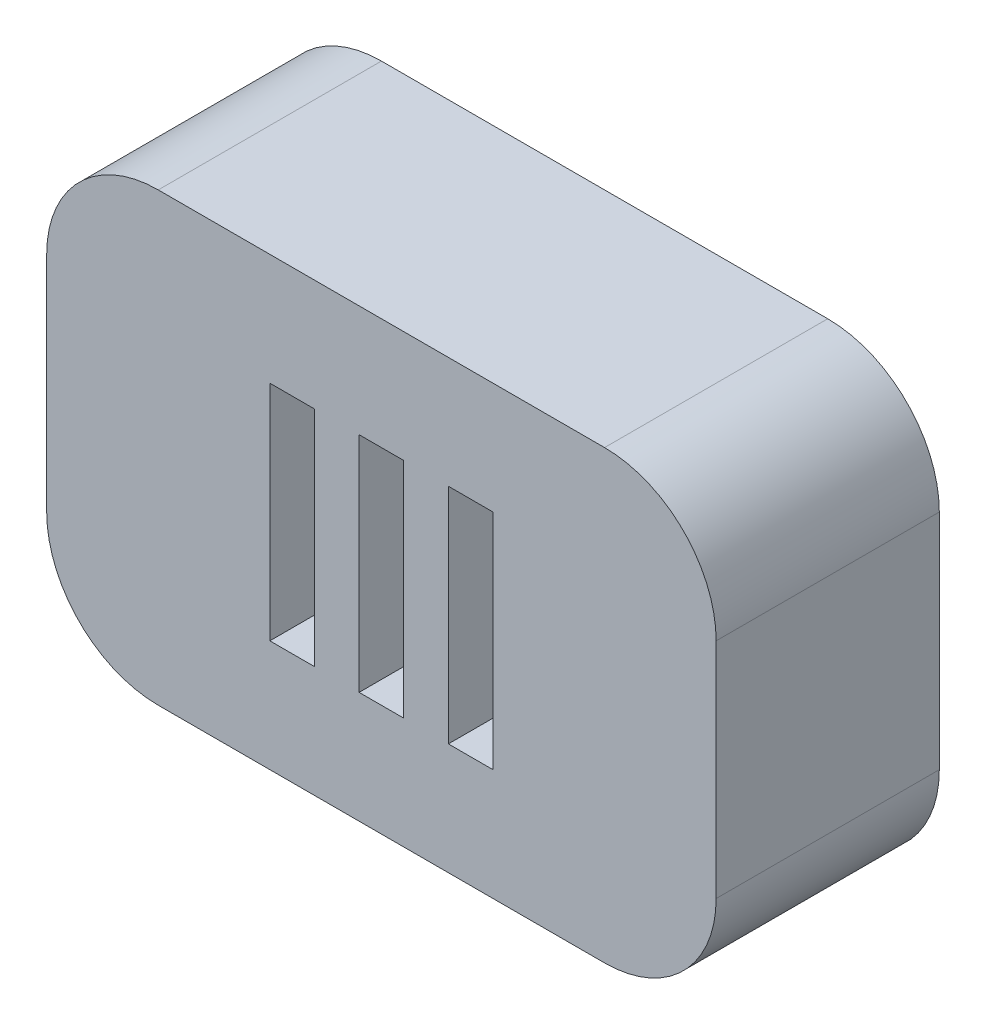
SolidWorks part; units mm, degrees
material "PVC hart"
ref_plane "Ebene vorne" through (0, 0, 0) normal (0, 0, 1) x (1, 0, 0)
ref_plane "Ebene oben" through (0, 0, 0) normal (0, 1, 0) x (1, 0, 0)
ref_plane "Ebene rechts" through (0, 0, 0) normal (1, 0, 0) x (0, 0, -1)
sketch "Skizze1" plane through (0, 0, 0) normal (0, 0, 1) x (1, 0, 0)
  line L1 (1, 0) -> (5, 0)
  line L2 (0, 1) -> (0, 3)
  line L3 (1, 4) -> (5, 4)
  line L4 (6, 1) -> (6, 3)
  arc A0 (0, 1) -> (1, 0) centre (1, 1) ccw
  arc A1 (5, 0) -> (6, 1) centre (5, 1) ccw
  arc A2 (6, 3) -> (5, 4) centre (5, 3) ccw
  arc A3 (1, 4) -> (0, 3) centre (1, 3) ccw
  point P7 (0, 0)
  point P10 (6, 0)
  point P13 (6, 4)
  dimension "D3" = 1
  dimension "D1" = 4
  dimension "D2" = 6
extrude "Aufsatz-Linear austragen1" add sketch "Skizze1" along normal blind 2
sketch "Skizze2" plane through (0, 0, 2) normal (0, 0, 1) x (1, 0, 0)
  line L0 (6, 1) -> (6, 3) construction
  line L1 (2.8, 3) -> (3.2, 3)
  line L2 (2.8, 3) -> (2.8, 1)
  line L3 (2.8, 1) -> (3.2, 1)
  line L4 (3.2, 3) -> (3.2, 1)
  line L5 (0, 3) -> (0, 1) construction
  line L6 (5, 4) -> (1, 4) construction
  line L7 (1, 0) -> (5, 0) construction
  dimension "D1" = 2.8
  dimension "D2" = 2.8
  dimension "D3" = 1
  dimension "D4" = 1
extrude "Schnitt-Linear austragen1" cut sketch "Skizze2" against normal blind 1
sketch "Skizze3" plane through (0, 0, 2) normal (0, 0, 1) x (1, 0, 0)
  line L0 (3.2, 1) -> (3.2, 3) construction
  line L1 (3.6, 3) -> (4, 3)
  line L2 (3.6, 3) -> (3.6, 1)
  line L3 (3.6, 1) -> (4, 1)
  line L4 (4, 3) -> (4, 1)
  line L5 (3.2, 3) -> (2.8, 3) construction
  line L6 (2.8, 1) -> (3.2, 1) construction
  dimension "D1" = 0.4
  dimension "D2" = 0.4
  dimension "D3" = 0
  dimension "D4" = 0
extrude "Schnitt-Linear austragen2" cut sketch "Skizze3" against normal blind 1
sketch "Skizze4" plane through (0, 0, 2) normal (0, 0, 1) x (1, 0, 0)
  line L0 (2.8, 3) -> (2.8, 1) construction
  line L1 (2.4, 3) -> (2, 3)
  line L2 (2.4, 3) -> (2.4, 1)
  line L3 (2.4, 1) -> (2, 1)
  line L4 (2, 3) -> (2, 1)
  line L5 (3.2, 3) -> (2.8, 3) construction
  line L6 (2.8, 1) -> (3.2, 1) construction
  dimension "D1" = 0.4
  dimension "D2" = 0.4
  dimension "D3" = 0
  dimension "D4" = 0
extrude "Schnitt-Linear austragen3" cut sketch "Skizze4" against normal blind 1
